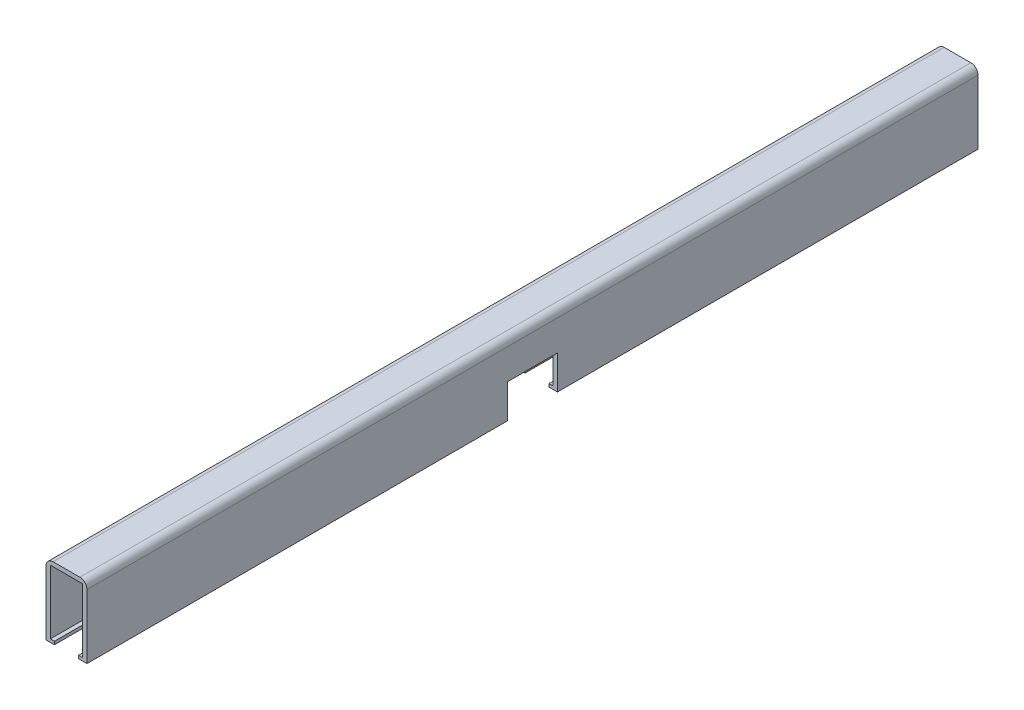
SolidWorks part; units mm, degrees
ref_plane "Front Plane" through (0, 0, 0) normal (0, 0, 1) x (1, 0, 0)
ref_plane "Top Plane" through (0, 0, 0) normal (0, 1, 0) x (1, 0, 0)
ref_plane "Right Plane" through (0, 0, 0) normal (1, 0, 0) x (0, 0, -1)
sketch "Sketch1" plane through (0, 0, 0) normal (0, 0, 1) x (1, 0, 0)
  line L0 (0, 0) -> (0, 40) construction
  line L1 (6.785, 0) -> (6.785, 1.73)
  line L2 (6.785, 0) -> (11.5, 0)
  line L3 (11.5, 0) -> (11.5, 36)
  line L4 (6.785, 1.73) -> (9.07, 1.73)
  line L5 (9.07, 1.73) -> (9.07, 37.58)
  line L6 (7.5, 40) -> (-7.5, 40)
  line L7 (9.07, 37.58) -> (-9.07, 37.58)
  line L8 (-9.07, 1.73) -> (-9.07, 37.58)
  line L9 (-6.785, 1.73) -> (-9.07, 1.73)
  line L10 (-11.5, 0) -> (-11.5, 36)
  line L11 (-6.785, 0) -> (-11.5, 0)
  line L12 (-6.785, 0) -> (-6.785, 1.73)
  arc A0 (11.5, 36) -> (7.5, 40) centre (7.5, 36) ccw
  arc A1 (-11.5, 36) -> (-7.5, 40) centre (-7.5, 36) cw
  point P16 (0, 37.58)
  dimension "D7" = 4
  dimension "D1" = 40
  dimension "D2" = 13.57
  dimension "D3" = 23
  dimension "D4" = 1.73
  dimension "D5" = 2.43
  dimension "D6" = 2.42
extrude "Boss-Extrude1" add sketch "Sketch1" along normal mid plane 500
sketch "Sketch2" plane through (0, 0, 0) normal (1, 0, 0) x (0, 0, -1)
  line L0 (-250, 0) -> (250, 0) construction
  line L1 (-14, 19) -> (14, 19)
  line L2 (-14, 19) -> (-14, 0)
  line L3 (-14, 0) -> (14, 0)
  line L4 (14, 19) -> (14, 0)
  point P6 (0, 0)
  dimension "D1" = 28
  dimension "D2" = 19
extrude "Cut-Extrude1" cut sketch "Sketch2" against normal up to next and the other way up to next
